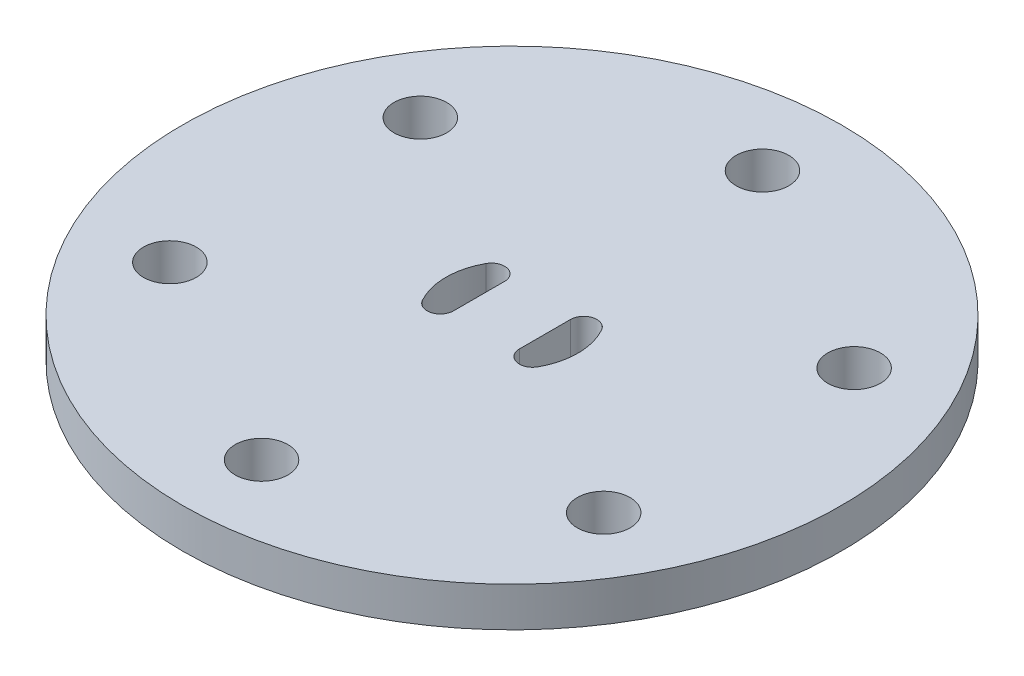
SolidWorks part; units mm, degrees
ref_plane "前视基准面" through (0, 0, 0) normal (0, 0, 1) x (1, 0, 0)
ref_plane "上视基准面" through (0, 0, 0) normal (0, 1, 0) x (1, 0, 0)
ref_plane "右视基准面" through (0, 0, 0) normal (1, 0, 0) x (0, 0, -1)
other "Configuration Table"
sketch "草图1" plane through (0, 0, 0) normal (0, 1, 0) x (1, 0, 0)
  circle A0 centre (0, 0) radius 25
  circle A2 centre (0, 19) radius 2
  circle A3 centre (16.4545, 9.5) radius 2
  circle A4 centre (16.4545, -9.5) radius 2
  circle A5 centre (0, -19) radius 2
  circle A6 centre (-16.4545, -9.5) radius 2
  circle A7 centre (-16.4545, 9.5) radius 2
  circle A8 centre (0, 0) radius 5
  point P17 (0, 0)
  dimension "D1" = 50
  dimension "D2" = 19
  dimension "D3" = 4
  dimension "D5" = 10
  dimension "D4" = 6
extrude "凸台-拉伸1" add sketch "草图1" along normal blind 3
sketch "草图2" plane through (0, 3, 0) normal (0, 1, 0) x (1, 0, 0)
  line L1 (-2.5, -6) -> (2.5, -6)
  line L2 (-2.5, -6) -> (-2.5, 6)
  line L3 (-2.5, 6) -> (2.5, 6)
  line L4 (2.5, -6) -> (2.5, 6)
  line L5 (-2.5, -6) -> (2.5, 6) construction
  line L6 (-2.5, 6) -> (2.5, -6) construction
  point P0 (0, 0)
  dimension "D1" = 5
  dimension "D2" = 12
extrude "凸台-拉伸2" add sketch "草图2" against normal blind 3
fillet "圆角1" radius 1 4 edges at (2.5, 1.5, 4.3301) (2.5, 1.5, -4.3301) (-2.5, 1.5, -4.3301) (-2.5, 1.5, 4.3301)
